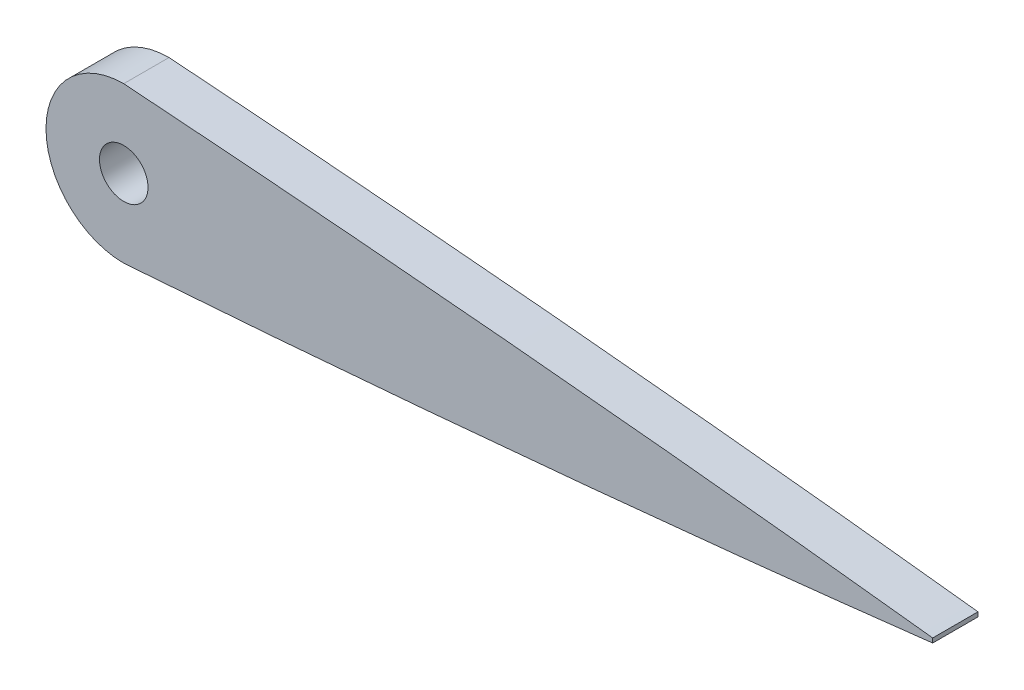
SolidWorks part; units mm, degrees
material "Фанера"
ref_plane "Спереди" through (0, 0, 0) normal (0, 0, 1) x (1, 0, 0)
ref_plane "Сверху" through (0, 0, 0) normal (0, 1, 0) x (1, 0, 0)
ref_plane "Справа" through (0, 0, 0) normal (1, 0, 0) x (0, 0, -1)
curve "Кривая1"
  spline degree 3 poles (200, 0.1365, 0) (199.688, 0.1729, 0) (198.8167, 0.2745, 0) (197.2359, 0.4561, 0) (195.145, 0.6923, 0) (192.7015, 0.9625, 0) (189.9816, 1.2561, 0) (187.0365, 1.566, 0) (183.905, 1.8867, 0) (180.6179, 2.2137, 0) (177.2012, 2.5436, 0) (173.6771, 2.8733, 0) (170.065, 3.2002, 0) (166.3822, 3.5221, 0) (162.6444, 3.8368, 0) (158.8659, 4.1424, 0) (155.06, 4.437, 0) (151.2387, 4.7189, 0) (147.4135, 4.9862, 0) (143.595, 5.2374, 0) (139.7935, 5.4706, 0) (136.0183, 5.6841, 0) (132.2786, 5.8765, 0) (128.5831, 6.0459, 0) (124.94, 6.191, 0) (121.3572, 6.3103, 0) (117.8424, 6.4025, 0) (114.4029, 6.4663, 0) (111.0457, 6.5008, 0) (107.7777, 6.505, 0) (104.6056, 6.4782, 0) (101.5356, 6.4201, 0) (98.5742, 6.3302, 0) (95.7272, 6.2086, 0) (93.0006, 6.0555, 0) (90.4002, 5.8711, 0) (87.9314, 5.6561, 0) (85.5998, 5.4114, 0) (83.4106, 5.1378, 0) (81.3691, 4.8365, 0) (79.4802, 4.5088, 0) (77.7488, 4.156, 0) (76.1798, 3.7796, 0) (74.7776, 3.3811, 0) (73.5467, 2.9618, 0) (72.4905, 2.523, 0) (71.6134, 2.0657, 0) (70.9148, 1.5895, 0) (70.4055, 1.0913, 0) (70.0654, 0.5615, 0) (70.0211, 0.181, 0) (70, 0, 0) knots 0 0 0 0 0.007145 0.019956 0.036196 0.055011 0.075879 0.098429 0.122376 0.147488 0.173572 0.20046 0.228005 0.256076 0.284555 0.313333 0.34231 0.371393 0.400496 0.429538 0.458442 0.487136 0.515552 0.543624 0.57129 0.598491 0.62517 0.651272 0.676746 0.701542 0.725611 0.748908 0.771388 0.793008 0.813728 0.833508 0.85231 0.870097 0.886836 0.902493 0.917037 0.930441 0.94268 0.953734 0.96359 0.972247 0.979722 0.986065 0.991385 0.995901 1 1 1 1
curve "Кривая2"
  spline degree 3 poles (70, 0, 0) (70.0211, -0.181, 0) (70.0654, -0.5615, 0) (70.4055, -1.0913, 0) (70.9148, -1.5895, 0) (71.6134, -2.0657, 0) (72.4905, -2.523, 0) (73.5467, -2.9618, 0) (74.7776, -3.3811, 0) (76.1798, -3.7796, 0) (77.7488, -4.156, 0) (79.4802, -4.5088, 0) (81.3691, -4.8365, 0) (83.4106, -5.1378, 0) (85.5998, -5.4114, 0) (87.9314, -5.6561, 0) (90.4002, -5.8711, 0) (93.0006, -6.0555, 0) (95.7272, -6.2086, 0) (98.5742, -6.3302, 0) (101.5356, -6.4201, 0) (104.6056, -6.4782, 0) (107.7777, -6.505, 0) (111.0457, -6.5008, 0) (114.4029, -6.4663, 0) (117.8424, -6.4025, 0) (121.3572, -6.3103, 0) (124.94, -6.191, 0) (128.5831, -6.0459, 0) (132.2786, -5.8765, 0) (136.0183, -5.6841, 0) (139.7935, -5.4706, 0) (143.595, -5.2374, 0) (147.4135, -4.9862, 0) (151.2387, -4.7189, 0) (155.06, -4.437, 0) (158.8659, -4.1424, 0) (162.6444, -3.8368, 0) (166.3822, -3.5221, 0) (170.065, -3.2002, 0) (173.6771, -2.8733, 0) (177.2012, -2.5436, 0) (180.6179, -2.2137, 0) (183.905, -1.8867, 0) (187.0365, -1.566, 0) (189.9816, -1.2561, 0) (192.7015, -0.9625, 0) (195.145, -0.6923, 0) (197.2359, -0.4561, 0) (198.8167, -0.2745, 0) (199.688, -0.1729, 0) (200, -0.1365, 0) knots 0 0 0 0 0.004099 0.008615 0.013935 0.020278 0.027753 0.03641 0.046266 0.05732 0.069559 0.082963 0.097507 0.113164 0.129903 0.14769 0.166492 0.186272 0.206992 0.228612 0.251092 0.274389 0.298458 0.323254 0.348728 0.37483 0.401509 0.42871 0.456376 0.484448 0.512864 0.541558 0.570462 0.599504 0.628607 0.65769 0.686667 0.715445 0.743924 0.771995 0.79954 0.826428 0.852512 0.877624 0.901571 0.924121 0.944989 0.963804 0.980044 0.992855 1 1 1 1
sketch "Эскиз1" plane through (0, 0, 0) normal (0, 0, 1) x (1, 0, 0)
  line L0 (200, 0.1365) -> (200, -0.1365)
  line L1 (100.4, -6.3839) -> (100.4, -3.2866)
  line L2 (100.4, -3.2866) -> (97.6, -3.2866)
  line L3 (97.6, -3.2866) -> (97.6, -6.2866)
  line L4 (124, 6.2207) -> (124, 3.116)
  line L5 (124, 3.116) -> (126.8, 3.116)
  line L6 (126.8, 3.116) -> (126.8, 6.116)
  circle A0 centre (109, 0) radius 4
  arc A1 (150, 4.8046) -> (150, -4.8046) centre (150, 0) ccw
  arc A2 (142.9507, 5.2753) -> (142.9507, -5.2753) centre (150, 0) ccw
  circle A4 centre (150, 0) radius 1.5
  spline S0 degree 3 poles (-6604.9726, -2096.9549) (186.3332, 58.0177) (64.4426, 8.1991) (70.4055, -1.0913) (70.9148, -1.5895) (71.6134, -2.0657) (72.4905, -2.523) (73.5467, -2.9618) (74.7776, -3.3811) (76.1798, -3.7796) (77.7488, -4.156) (79.4802, -4.5088) (81.3691, -4.8365) (83.4106, -5.1378) (85.5998, -5.4114) (87.9314, -5.6561) (90.4002, -5.8711) (93.0006, -6.0555) (95.7272, -6.2086) (98.5742, -6.3302) (101.5356, -6.4201) (104.6056, -6.4782) (107.7777, -6.505) (111.0457, -6.5008) (114.4029, -6.4663) (117.8424, -6.4025) (121.3572, -6.3103) (124.94, -6.191) (128.5831, -6.0459) (132.2786, -5.8765) (136.0183, -5.6841) (139.7935, -5.4706) (143.595, -5.2374) (147.4135, -4.9862) (151.2387, -4.7189) (155.06, -4.437) (158.8659, -4.1424) (162.6444, -3.8368) (166.3822, -3.5221) (170.065, -3.2002) (174.8191, -2.7699) (179.4417, -2.3307) (183.905, -1.8867) (187.0365, -1.566) (189.9816, -1.2561) (192.7015, -0.9625) (195.145, -0.6923) (197.2359, -0.4561) (302.0269, 11.5824) (403.6317, 44.8697) (1315.1992, -6901.8264) knots -0.230414 -0.230414 -0.230414 -0.230414 0.004099 0.008615 0.013935 0.020278 0.027753 0.03641 0.046266 0.05732 0.069559 0.082963 0.097507 0.113164 0.129903 0.14769 0.166492 0.186272 0.206992 0.228612 0.251092 0.274389 0.298458 0.323254 0.348728 0.37483 0.401509 0.42871 0.456376 0.484448 0.512864 0.541558 0.570462 0.599504 0.628607 0.65769 0.686667 0.715445 0.743924 0.771995 0.79954 0.852512 0.877624 0.901571 0.924121 0.944989 0.963804 0.980044 0.992855 3.363271 3.363271 3.363271 3.363271 only from (70, 0) to (200, -0.1365) construction
  spline S1 degree 3 poles (1315.2065, 6901.882) (403.6322, -44.8698) (302.0272, -11.5824) (197.2359, 0.4561) (195.145, 0.6923) (192.7015, 0.9625) (189.9816, 1.2561) (187.0365, 1.566) (183.905, 1.8867) (179.4417, 2.3307) (174.8191, 2.7699) (170.065, 3.2002) (166.3822, 3.5221) (162.6444, 3.8368) (158.8659, 4.1424) (155.06, 4.437) (151.2387, 4.7189) (147.4135, 4.9862) (143.595, 5.2374) (139.7935, 5.4706) (136.0183, 5.6841) (132.2786, 5.8765) (128.5831, 6.0459) (124.94, 6.191) (121.3572, 6.3103) (117.8424, 6.4025) (114.4029, 6.4663) (111.0457, 6.5008) (107.7777, 6.505) (104.6056, 6.4782) (101.5356, 6.4201) (98.5742, 6.3302) (95.7272, 6.2086) (93.0006, 6.0555) (90.4002, 5.8711) (87.9314, 5.6561) (85.5998, 5.4114) (83.4106, 5.1378) (81.3691, 4.8365) (79.4802, 4.5088) (77.7488, 4.156) (76.1798, 3.7796) (74.7776, 3.3811) (73.5467, 2.9618) (72.4905, 2.523) (71.6134, 2.0657) (70.9148, 1.5895) (70.4055, 1.0913) (64.4431, -8.1984) (186.3138, -58.0097) (-6603.3138, 2096.4286) knots -2.363277 -2.363277 -2.363277 -2.363277 0.007145 0.019956 0.036196 0.055011 0.075879 0.098429 0.122376 0.147488 0.20046 0.228005 0.256076 0.284555 0.313333 0.34231 0.371393 0.400496 0.429538 0.458442 0.487136 0.515552 0.543624 0.57129 0.598491 0.62517 0.651272 0.676746 0.701542 0.725611 0.748908 0.771388 0.793008 0.813728 0.833508 0.85231 0.870097 0.886836 0.902493 0.917037 0.930441 0.94268 0.953734 0.96359 0.972247 0.979722 0.986065 0.991385 0.995901 1.230395 1.230395 1.230395 1.230395 only from (200, 0.1365) to (70, 0) construction
  spline S2 degree 3 poles (70, 0) (70.0211, -0.181) (70.0654, -0.5615) (70.4055, -1.0913) (70.9148, -1.5895) (71.6134, -2.0657) (72.4905, -2.523) (73.5467, -2.9618) (74.7776, -3.3811) (76.1798, -3.7796) (77.7488, -4.156) (79.4802, -4.5088) (81.3691, -4.8365) (83.4106, -5.1378) (85.5998, -5.4114) (87.9314, -5.6561) (90.4002, -5.8711) (93.0006, -6.0555) (95.4152, -6.1911) (96.9625, -6.2607) (97.6, -6.2866) knots 0 0 0 0 0.004099 0.008615 0.013935 0.020278 0.027753 0.03641 0.046266 0.05732 0.069559 0.082963 0.097507 0.113164 0.129903 0.14769 0.166492 0.186272 0.206992 0.221505 0.221505 0.221505 0.221505
  spline S3 degree 3 poles (200, 0.1365) (199.688, 0.1729) (198.8167, 0.2745) (197.2359, 0.4561) (195.145, 0.6923) (192.7015, 0.9625) (189.9816, 1.2561) (187.0365, 1.566) (183.905, 1.8867) (179.4417, 2.3307) (174.8191, 2.7699) (170.065, 3.2002) (166.3822, 3.5221) (162.6444, 3.8368) (158.8659, 4.1424) (155.06, 4.437) (151.2387, 4.7189) (147.4135, 4.9862) (143.595, 5.2374) (139.7935, 5.4706) (136.0183, 5.6841) (132.2786, 5.8765) (129.2098, 6.0172) (127.3884, 6.0925) (126.8, 6.116) knots 0 0 0 0 0.007145 0.019956 0.036196 0.055011 0.075879 0.098429 0.122376 0.147488 0.20046 0.228005 0.256076 0.284555 0.313333 0.34231 0.371393 0.400496 0.429538 0.458442 0.487136 0.515552 0.543624 0.55702 0.55702 0.55702 0.55702
  spline S4 degree 3 poles (100.4, -6.3839) (100.7666, -6.3946) (102.157, -6.4319) (104.6056, -6.4782) (107.7777, -6.505) (111.0457, -6.5008) (114.4029, -6.4663) (117.8424, -6.4025) (121.3572, -6.3103) (124.94, -6.191) (128.5831, -6.0459) (132.2786, -5.8765) (136.0183, -5.6841) (139.7935, -5.4706) (143.595, -5.2374) (147.4135, -4.9862) (151.2387, -4.7189) (155.06, -4.437) (158.8659, -4.1424) (162.6444, -3.8368) (166.3822, -3.5221) (170.065, -3.2002) (174.8191, -2.7699) (179.4417, -2.3307) (183.905, -1.8867) (187.0365, -1.566) (189.9816, -1.2561) (192.7015, -0.9625) (195.145, -0.6923) (197.2359, -0.4561) (198.8167, -0.2745) (199.688, -0.1729) (200, -0.1365) knots 0.242749 0.242749 0.242749 0.242749 0.251092 0.274389 0.298458 0.323254 0.348728 0.37483 0.401509 0.42871 0.456376 0.484448 0.512864 0.541558 0.570462 0.599504 0.628607 0.65769 0.686667 0.715445 0.743924 0.771995 0.79954 0.852512 0.877624 0.901571 0.924121 0.944989 0.963804 0.980044 0.992855 1 1 1 1
  spline S5 degree 3 poles (124, 6.2207) (123.1115, 6.2516) (121.0507, 6.3184) (117.8424, 6.4025) (114.4029, 6.4663) (111.0457, 6.5008) (107.7777, 6.505) (104.6056, 6.4782) (101.5356, 6.4201) (98.5742, 6.3302) (95.7272, 6.2086) (93.0006, 6.0555) (90.4002, 5.8711) (87.9314, 5.6561) (85.5998, 5.4114) (83.4106, 5.1378) (81.3691, 4.8365) (79.4802, 4.5088) (77.7488, 4.156) (76.1798, 3.7796) (74.7776, 3.3811) (73.5467, 2.9618) (72.4905, 2.523) (71.6134, 2.0657) (70.9148, 1.5895) (70.4055, 1.0913) (70.0654, 0.5615) (70.0211, 0.181) (70, 0) knots 0.578266 0.578266 0.578266 0.578266 0.598491 0.62517 0.651272 0.676746 0.701542 0.725611 0.748908 0.771388 0.793008 0.813728 0.833508 0.85231 0.870097 0.886836 0.902493 0.917037 0.930441 0.94268 0.953734 0.96359 0.972247 0.979722 0.986065 0.991385 0.995901 1 1 1 1
  point P13 (99, -3.2866)
  dimension "D1" = 8
  dimension "D11" = 4.8046
  dimension "D12" = 8.8046
  dimension "D13" = 3
  dimension "D2" = 39
  dimension "D8" = 2.8
  dimension "D9" = 10
  dimension "D3" = 3
  dimension "D4" = 2.8
  dimension "D5" = 15
  dimension "D6" = 3
  dimension "D10" = 80
  dimension "D7" = 9.6092
extrude "Бобышка-Вытянуть1" add sketch "Эскиз1" along normal mid plane 2.8 contours A1 S4 L0 S3 A4
equation "\"D11@Эскиз1\"=\"D7@Эскиз1\"/2"
equation "\"D12@Эскиз1\"=\"D11@Эскиз1\"+4"
